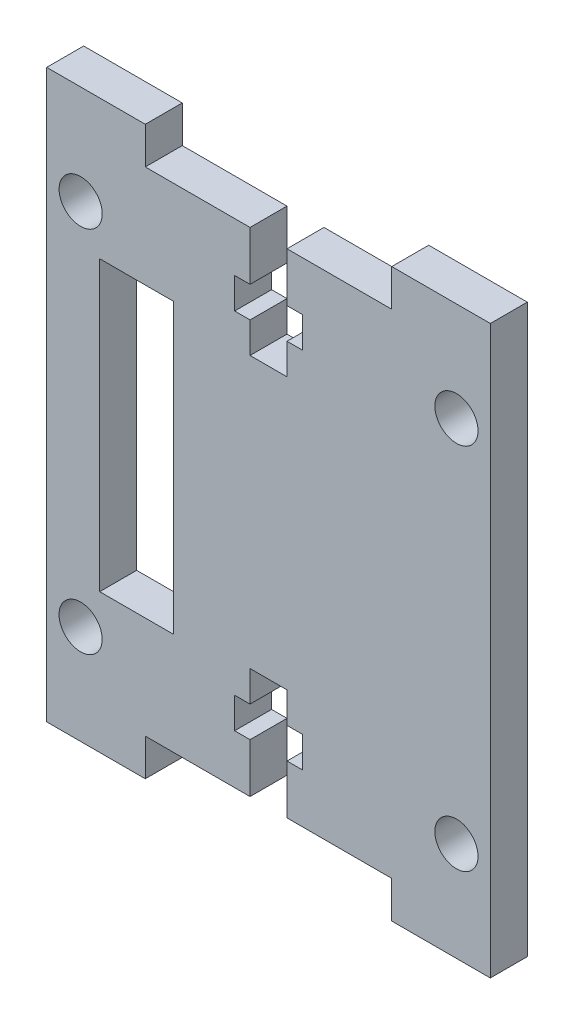
SolidWorks part; units mm, degrees
material "Pinho"
ref_plane "Plano frontal" through (0, 0, 0) normal (0, 0, 1) x (1, 0, 0)
ref_plane "Plano superior" through (0, 0, 0) normal (0, 1, 0) x (1, 0, 0)
ref_plane "Plano direito" through (0, 0, 0) normal (1, 0, 0) x (0, 0, -1)
sketch "Esboço1" plane through (0, 0, 0) normal (0, 0, 1) x (1, 0, 0)
  line L0 (2.25, 0) -> (-6.25, 0)
  line L1 (-6.25, 0) -> (-6.25, 2)
  line L2 (5.25, 0) -> (13.75, 0)
  line L3 (13.75, 0) -> (13.75, 2)
  line L4 (13.75, -42) -> (13.75, -43)
  line L6 (21.75, 2) -> (21.75, -42)
  line L7 (2.25, -4) -> (2.25, 0)
  line L8 (1, -4) -> (2.25, -4)
  line L9 (-14.25, 2) -> (-14.25, -42)
  line L11 (21.75, -42) -> (21.75, -43)
  line L12 (-14.25, -42) -> (-14.25, -43)
  line L14 (-6.25, -42) -> (-6.25, -43)
  line L15 (1, -36) -> (1, -33.5)
  line L16 (1, -33.5) -> (2.25, -33.5)
  line L17 (2.25, -31) -> (5.25, -31)
  line L18 (5.25, -4) -> (5.25, 0)
  line L19 (6.5, -4) -> (5.25, -4)
  line L20 (6.5, -6.5) -> (6.5, -4)
  line L21 (5.25, -6.5) -> (6.5, -6.5)
  line L22 (5.25, -9) -> (5.25, -6.5)
  line L23 (2.25, -6.5) -> (2.25, -9)
  line L24 (2.25, -9) -> (5.25, -9)
  line L25 (1, -6.5) -> (2.25, -6.5)
  line L26 (1, -4) -> (1, -6.5)
  line L27 (2.25, -33.5) -> (2.25, -31)
  line L28 (5.25, -31) -> (5.25, -33.5)
  line L29 (5.25, -33.5) -> (6.5, -33.5)
  line L30 (6.5, -33.5) -> (6.5, -36)
  line L31 (6.5, -36) -> (5.25, -36)
  line L32 (5.25, -36) -> (5.25, -40)
  line L33 (1, -36) -> (2.25, -36)
  line L34 (2.25, -36) -> (2.25, -40)
  line L35 (13.75, -40) -> (13.75, -42)
  line L36 (5.25, -40) -> (13.75, -40)
  line L37 (-6.25, -40) -> (-6.25, -42)
  line L38 (2.25, -40) -> (-6.25, -40)
  line L39 (-6.25, 2) -> (-6.25, 3)
  line L42 (-14.25, 2) -> (-14.25, 3)
  line L43 (21.75, 3) -> (13.75, 3)
  line L44 (21.75, -43) -> (13.75, -43)
  line L45 (21.75, 2) -> (21.75, 3)
  line L47 (13.75, 2) -> (13.75, 3)
  line L48 (-6.25, 3) -> (-14.25, 3)
  line L49 (-6.25, -43) -> (-14.25, -43)
  line L53 (-9.95, -8.8) -> (-9.95, -31.2)
  line L54 (-3.95, -8.8) -> (-3.95, -31.2)
  line L64 (-6.95, -31.7) -> (-9.95, -31.7)
  line L65 (-9.95, -31.7) -> (-9.95, -31.2)
  line L66 (-6.95, -31.7) -> (-3.95, -31.7)
  line L67 (-3.95, -31.7) -> (-3.95, -31.2)
  line L68 (-6.95, -8.3) -> (-9.95, -8.3)
  line L69 (-9.95, -8.3) -> (-9.95, -8.8)
  line L70 (-6.95, -8.3) -> (-3.95, -8.3)
  line L71 (-3.95, -8.3) -> (-3.95, -8.8)
  circle A0 centre (19, -5.05) radius 1.75
  circle A5 centre (-11.495, -5.05) radius 1.75
  circle A6 centre (19, -34.95) radius 1.75
  circle A7 centre (-11.5, -34.95) radius 1.75
  point P37 (-14.25, -20)
  point P39 (21.75, -20)
extrude "Ressalto-extrusão1" add sketch "Esboço1" along normal blind 3
